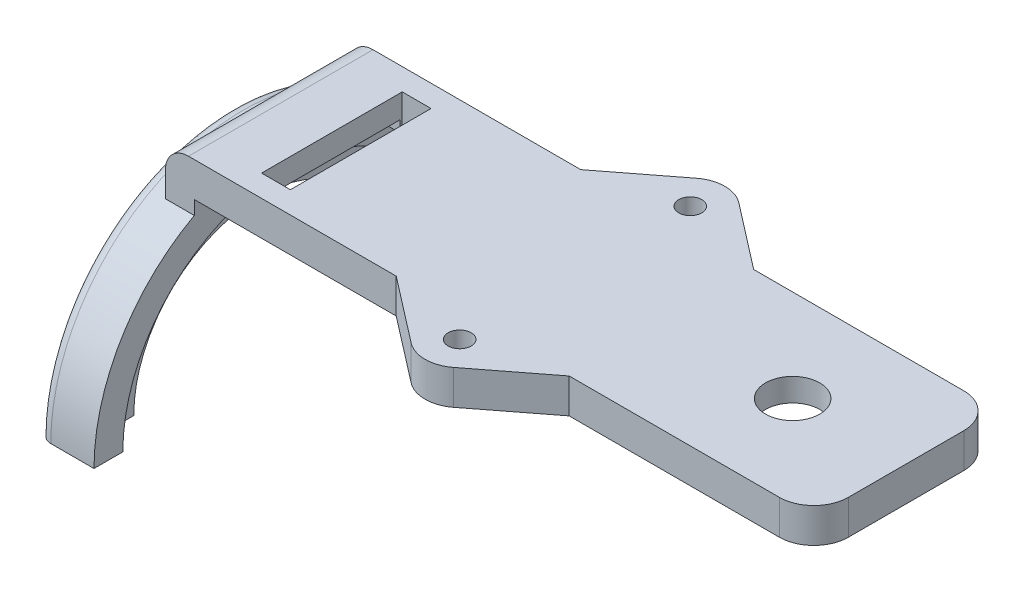
SolidWorks part; units mm, degrees
material "ABS"
ref_plane "Front" through (0, 0, 0) normal (0, 0, 1) x (1, 0, 0)
ref_plane "Top" through (0, 0, 0) normal (0, 1, 0) x (1, 0, 0)
ref_plane "Right" through (0, 0, 0) normal (1, 0, 0) x (0, 0, -1)
sketch "Sketch1" plane through (0, 0, 0) normal (0, 1, 0) x (1, 0, 0)
  line L0 (4.5, 8) -> (27.1, 8) construction
  line L2 (6.435, 14.1) -> (8.935, 14.1)
  line L3 (6.435, 14.1) -> (6.435, 1.9)
  line L4 (6.435, 1.9) -> (8.935, 1.9)
  line L5 (56.235, 0) -> (56.235, 16)
  line L6 (0, 16) -> (56.235, 16)
  line L7 (0, 16) -> (0, 0)
  line L8 (0, 0) -> (56.235, 0)
  line L9 (8.935, 14.1) -> (8.935, 1.9)
  circle A2 centre (46.395, 8) radius 2.35
  point P6 (7.685, 1.9)
  dimension "D1" = 16
  dimension "D2" = 7.685
  dimension "D5" = 49.8
  dimension "D7" = 9.84
  dimension "D8" = 4.7
  dimension "D3" = 12.2
  dimension "D6" = 8
  dimension "D4" = 2.5
extrude "Boss-Extrude1" add sketch "Sketch1" along normal blind 3
sketch "Esquisse3" plane through (0, 0, 0) normal (0, -1, 0) x (1, 0, 0)
  line L4 (0, -2.08) -> (0, -13.92)
  line L5 (56.235, 0) -> (56.235, -16) construction
  line L6 (0, -13.92) -> (22.7, -13.92)
  line L7 (0, -2.08) -> (22.7, -2.08)
  line L8 (29.635, -13.92) -> (52.235, -13.92)
  line L9 (52.235, -13.92) -> (52.235, -2.08)
  line L10 (52.235, -2.08) -> (29.635, -2.08)
  line L11 (29.635, -2.08) -> (29.635, -13.92)
  line L12 (52.235, -8) -> (9.3299, -8) construction
  line L13 (0, -16) -> (56.235, -16) construction
  line L14 (0, 0) -> (56.235, 0) construction
  line L15 (0, -16) -> (0, 0) construction
  line L30 (22.7, -2.08) -> (22.7, -13.92)
  dimension "D1" = 4
  dimension "D2" = 22.6
  dimension "D3" = 22.7
  dimension "D4" = 11.84
extrude "Enlèv. mat.-Extru.1" cut sketch "Esquisse3" against normal blind 1
sketch "Esquisse4" plane through (0, 3, 0) normal (0, 1, 0) x (1, 0, 0)
  line L0 (56.235, 0) -> (56.235, 16) construction
  line L1 (0, 16) -> (56.235, 16) construction
  line L2 (20.015, 16) -> (25.6817, 20.3747)
  line L3 (29.3483, 20.3747) -> (35.015, 16)
  line L4 (27.515, 23.1403) -> (27.515, 13.084) construction
  line L5 (6.435, 8) -> (56.235, 8) construction
  line L6 (20.015, 16) -> (27.515, 16)
  line L7 (27.515, 16) -> (35.015, 16)
  line L8 (6.435, 14.1) -> (6.435, 1.9) construction
  line L9 (56.235, 0) -> (56.235, 16) construction
  line L10 (27.515, 0) -> (35.015, 0)
  line L11 (20.015, 0) -> (27.515, 0)
  line L12 (29.3483, -4.3747) -> (35.015, 0)
  line L13 (20.015, 0) -> (25.6817, -4.3747)
  line L14 (8.935, 14.1) -> (8.935, 1.9) construction
  arc A0 (29.3483, 20.3747) -> (25.6817, 20.3747) centre (27.515, 18) ccw
  circle A1 centre (27.515, 18) radius 1
  circle A2 centre (27.515, -2) radius 1
  arc A3 (29.3483, -4.3747) -> (25.6817, -4.3747) centre (27.515, -2) cw
  dimension "D3" = 2
  dimension "D4" = 6
  dimension "D1" = 18.58
  dimension "D2" = 2
  dimension "D5" = 15
  dimension "D6" = 2
extrude "Boss.-Extru.2" add sketch "Esquisse4" against normal blind 3
ref_plane "Plan1" through (0, 0, -8) normal (0, 0, 1) x (1, 0, 0)
sketch "Esquisse5" plane through (0, 0, -8) normal (0, 0, 1) x (1, 0, 0)
  line L0 (-14.2376, -15.86) -> (-32.7654, -15.86) construction
  line L1 (-2.25, 0.84) -> (2.5, 0.84)
  line L2 (2.5, 0.84) -> (2.5, -1.66)
  line L4 (2.5, -1.66) -> (0.25, -1.66)
  line L6 (0.25, -1.66) -> (0.25, -4.86)
  line L7 (0.25, -4.86) -> (-2.25, -4.86)
  line L9 (-2.25, -4.86) -> (-2.25, 0.84)
  line L15 (-2.9, -15.86) -> (-43.9977, -15.86) construction
  dimension "D1" = 11
  dimension "D2" = 2.25
  dimension "D3" = 2.5
  dimension "D4" = 14.2
  dimension "D5" = 2.5
  dimension "D6" = 4
revolve "Révolution1" add sketch "Esquisse5" angle 90 about L0
sketch "Esquisse6" plane through (0, 3, 0) normal (0, 1, 0) x (1, 0, 0)
  line L0 (0, 0) -> (20.015, 0) construction
  line L1 (0, 16) -> (2.5, 16)
  line L2 (0, 16) -> (0, 0)
  line L3 (0, 0) -> (2.5, 0)
  line L4 (2.5, 16) -> (2.5, 0)
  dimension "D1" = 2.5
extrude "Boss.-Extru.3" add sketch "Esquisse6" against normal blind 4.8
fillet "Congé1" radius 2 1 edges at (0, 3, -8)
fillet "Congé2" radius 3 2 edges at (56.235, 1.5, 0) (56.235, 1.5, -16)
fillet "Congé3" radius 1 1 edges at (-2.25, 0.84, -8)
